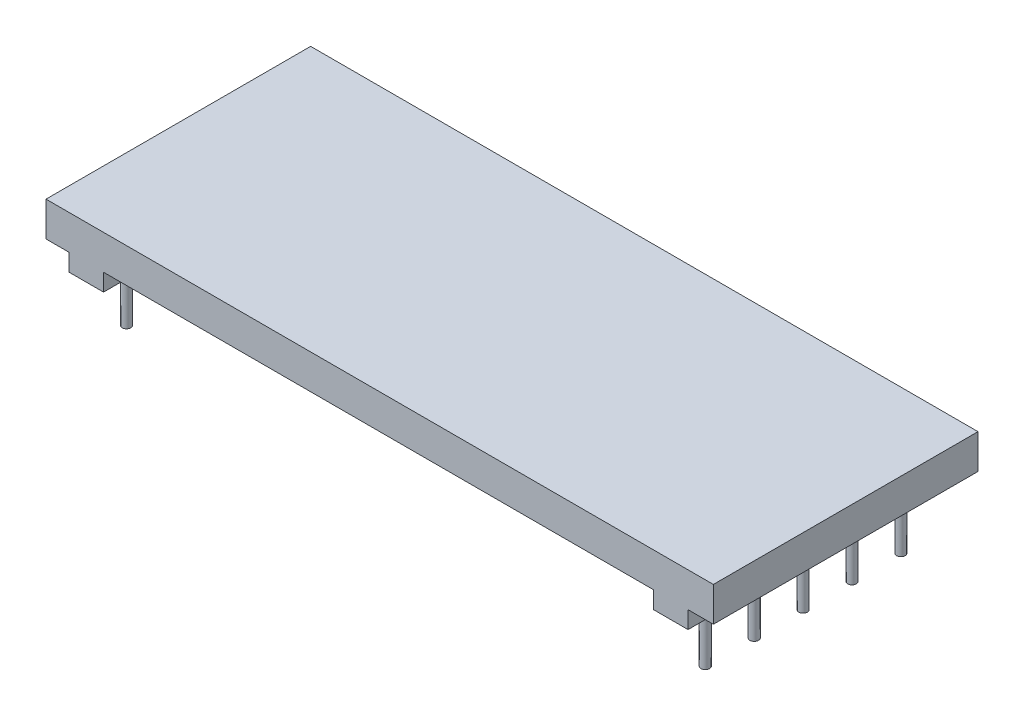
SolidWorks part; units mm, degrees
ref_plane "Front Plane" through (0, 0, 0) normal (0, 0, 1) x (1, 0, 0)
ref_plane "Top Plane" through (0, 0, 0) normal (0, 1, 0) x (1, 0, 0)
ref_plane "Right Plane" through (0, 0, 0) normal (1, 0, 0) x (0, 0, -1)
sketch "Sketch1" plane through (0, 0, 0) normal (0, 1, 0) x (1, 0, 0)
  line L1 (-29, 11.5) -> (29, 11.5)
  line L2 (-29, 11.5) -> (-29, -11.5)
  line L3 (-29, -11.5) -> (29, -11.5)
  line L4 (29, 11.5) -> (29, -11.5)
  line L5 (-29, 11.5) -> (29, -11.5) construction
  line L6 (-29, -11.5) -> (29, 11.5) construction
  point P0 (0, 0)
  dimension "D1" = 58
  dimension "D2" = 23
extrude "Boss-Extrude1" add sketch "Sketch1" along normal blind 3
sketch "Sketch2" plane through (0, 0, 0) normal (0, -1, 0) x (1, 0, 0)
  line L0 (-29, 11.5) -> (29, 11.5) construction
  line L1 (-27, 11.5) -> (-24, 11.5)
  line L2 (-27, 11.5) -> (-27, -11.5)
  line L3 (-27, -11.5) -> (-24, -11.5)
  line L4 (-24, 11.5) -> (-24, -11.5)
  line L5 (29, -11.5) -> (-29, -11.5) construction
  line L6 (-29, -11.5) -> (-29, 11.5) construction
  line L7 (-25.5, 11.5) -> (-25.5, -11.5) construction
  point P8 (-29, 0)
  dimension "D1" = 3
  dimension "D2" = 2
extrude "Boss-Extrude2" add sketch "Sketch2" along normal blind 1.5
sketch "Sketch3" plane through (0, -1.5, 0) normal (0, -1, 0) x (1, 0, 0)
  line L0 (-25.5, 11.5) -> (-25.5, -11.5) construction
  line L1 (-24, 11.5) -> (-27, 11.5) construction
  line L2 (-27, -11.5) -> (-24, -11.5) construction
  line L3 (-25.5, 3.5) -> (-25.5, -19.5) construction
  line L4 (-25.5, -4.5) -> (-25.5, -27.5) construction
  line L5 (-27, 11.5) -> (-27, -11.5) construction
  circle A0 centre (-25.5, 8) radius 0.375
  circle A1 centre (-25.5, 0) radius 0.375
  circle A2 centre (-25.5, -8) radius 0.375
  dimension "D1" = 0.75
  dimension "D2" = 3.5
  dimension "D4" = 11.5
  dimension "D5" = 1.5
  dimension "D3" = 3
extrude "Boss-Extrude3" add sketch "Sketch3" along normal blind 5
pattern_linear "LPattern1" count 2 spacing 50.8 along (1, 0, 0) of "Boss-Extrude2"
sketch "Sketch4" plane through (0, -1.5, 0) normal (0, -1, 0) x (1, 0, 0)
  line L0 (25.3, 11.5) -> (25.3, -11.5) construction
  line L1 (26.8, 11.5) -> (23.8, 11.5) construction
  line L2 (23.8, -11.5) -> (26.8, -11.5) construction
  line L3 (23.8, 11.5) -> (23.8, -11.5) construction
  circle A0 centre (25.3, 8.5) radius 0.375
  circle A1 centre (25.3, 4.25) radius 0.375
  circle A2 centre (25.3, 0) radius 0.375
  circle A3 centre (25.3, -4.25) radius 0.375
  circle A4 centre (25.3, -8.5) radius 0.375
  dimension "D1" = 0.75
  dimension "D2" = 3
  dimension "D4" = 1.5
  dimension "D5" = 7.25
  dimension "D3" = 5
extrude "Boss-Extrude4" add sketch "Sketch4" along normal blind 5
